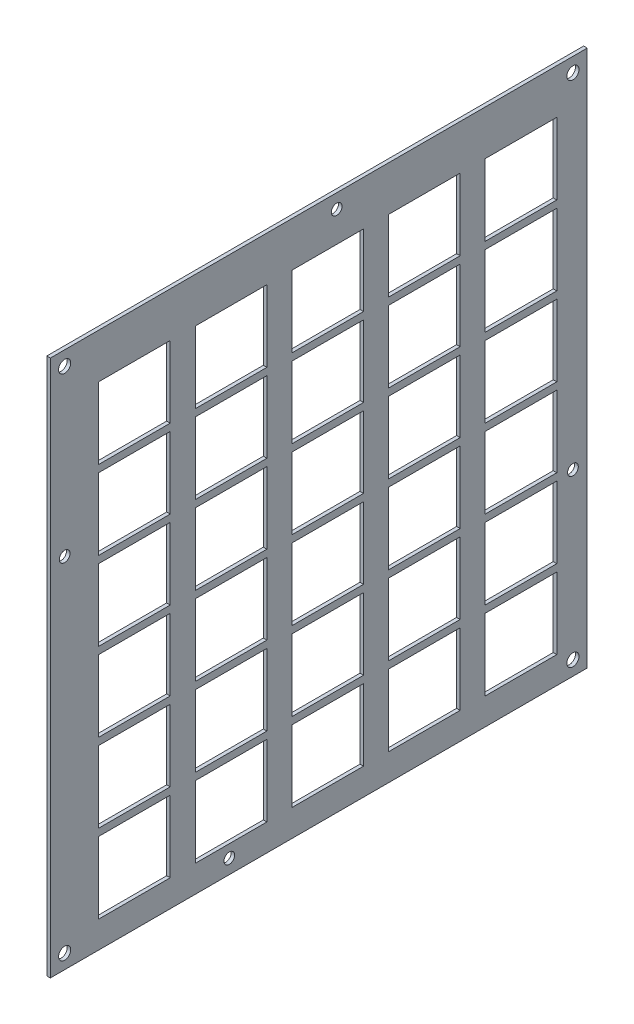
SolidWorks part; units mm, degrees
ref_plane "Front Plane" through (0, 0, 0) normal (0, 0, 1) x (1, 0, 0)
ref_plane "Top Plane" through (0, 0, 0) normal (0, 1, 0) x (1, 0, 0)
ref_plane "Right Plane" through (0, 0, 0) normal (1, 0, 0) x (0, 0, -1)
sketch "Sketch2" plane through (0, 0, 0) normal (1, 0, 0) x (0, 0, -1)
  line L1 (-40.899, 33.7667) -> (109.101, 33.7667)
  line L2 (-40.899, 33.7667) -> (-40.899, -116.2333)
  line L3 (-40.899, -116.2333) -> (109.101, -116.2333)
  line L4 (109.101, 33.7667) -> (109.101, -116.2333)
  dimension "D1" = 150
  dimension "D2" = 150
extrude "Boss-Extrude1" add sketch "Sketch2" along normal blind 1
sketch "Sketch3" plane through (1, 0, 0) normal (1, 0, 0) x (0, 0, -1)
  line L1 (-27.399, 21.2667) -> (-9.899, 21.2667)
  line L2 (-27.399, 21.2667) -> (-27.399, 3.7667)
  line L3 (-27.399, 3.7667) -> (-9.899, 3.7667)
  line L4 (-9.899, 21.2667) -> (-9.899, 3.7667)
  line L5 (-40.899, 33.7667) -> (-40.899, -116.2333) construction
  line L6 (109.101, 33.7667) -> (-40.899, 33.7667) construction
  dimension "D1" = 17.5
  dimension "D2" = 17.5
  dimension "D3" = 31
  dimension "D4" = 30
sketch "Sketch4" plane through (1, 0, 0) normal (1, 0, 0) x (0, 0, -1)
  line L1 (-27.399, 21.2667) -> (-7.399, 21.2667)
  line L2 (-27.399, 21.2667) -> (-27.399, 1.2667)
  line L3 (-27.399, 1.2667) -> (-7.399, 1.2667)
  line L4 (-7.399, 21.2667) -> (-7.399, 1.2667)
  dimension "D1" = 20
  dimension "D2" = 20
extrude "Cut-Extrude1" cut sketch "Sketch4" against normal through all
pattern_linear "LPattern1" count 5 spacing 27 along (0, 0, -1) count 6 spacing 22 along (0, -1, 0) of "Cut-Extrude1"
sketch "Sketch5" plane through (1, 0, 0) normal (1, 0, 0) x (0, 0, -1)
  line L0 (109.101, -116.2333) -> (109.101, 33.7667) construction
  line L1 (-40.899, -116.2333) -> (109.101, -116.2333) construction
  line L2 (109.101, 33.7667) -> (-40.899, 33.7667) construction
  line L3 (-40.899, 33.7667) -> (-40.899, -116.2333) construction
  point P0 (-36.899, 29.7667)
  point P1 (105.101, -112.2333)
  point P10 (105.101, 29.7667)
  point P11 (-36.899, -112.2333)
  dimension "D1" = 4
  dimension "D2" = 4
  dimension "D3" = 4
  dimension "D4" = 4
hole_wizard "M3 Clearance Hole1" positions "Sketch6" profile "Sketch7" hole size "M3" standard "ANSI Metric" end condition through all
sketch "Sketch6" plane through (1, 0, 0) normal (1, 0, 0) x (0, 0, -1)
  point P0 (-36.899, 29.7667)
  point P3 (105.101, 29.7667)
  point P6 (105.101, -112.2333)
  point P9 (-36.899, -112.2333)
sketch "Sketch7" plane through (1, 29.7667, 36.899) normal (0, 1, 0) x (0, 0, -1)
  line L0 (0, 0) -> (0, 1)
  line L1 (0, 1) -> (1.7, 1)
  line L2 (1.7, 1) -> (1.7, 0)
  line L5 (1.7, 0) -> (0, 0)
  line L11 (0, -6.35) -> (0, 107.95) construction
  dimension "Thru Hole Dia." = 3.4
  dimension "Thru Hole Depth" = 1
sketch "Sketch8" plane through (1, 0, 0) normal (1, 0, 0) x (0, 0, -1)
  line L0 (-40.899, 33.7667) -> (-40.899, -116.2333) construction
  line L5 (109.101, 33.7667) -> (-40.899, 33.7667) construction
  line L6 (-40.899, -116.2333) -> (109.101, -116.2333) construction
  line L7 (109.101, -116.2333) -> (109.101, 33.7667) construction
  circle A0 centre (39.101, 29.7667) radius 1.5
  circle A1 centre (-36.899, -16.2333) radius 1.5
  circle A2 centre (9.101, -112.2333) radius 1.5
  circle A3 centre (105.101, -66.2333) radius 1.5
  dimension "D1" = 3
  dimension "D4" = 3
  dimension "D9" = 3
  dimension "D10" = 3
  dimension "D2" = 80
  dimension "D3" = 4
  dimension "D5" = 4
  dimension "D6" = 50
  dimension "D7" = 50
  dimension "D8" = 4
  dimension "D11" = 50
  dimension "D12" = 4
extrude "Cut-Extrude2" cut sketch "Sketch8" against normal through all
